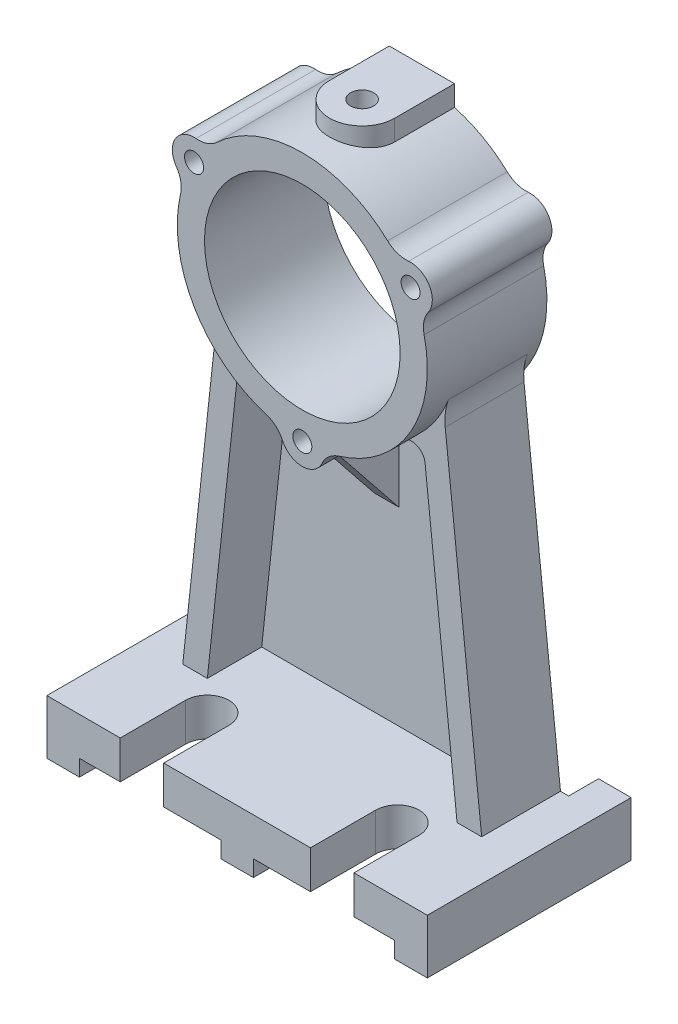
SolidWorks part; units mm, degrees
ref_plane "前视基准面" through (0, 0, 0) normal (0, 0, 1) x (1, 0, 0)
ref_plane "上视基准面" through (0, 0, 0) normal (0, 1, 0) x (1, 0, 0)
ref_plane "右视基准面" through (0, 0, 0) normal (1, 0, 0) x (0, 0, -1)
other "Configuration Table"
sketch "草图1" plane through (0, 0, 0) normal (0, 0, 1) x (1, 0, 0)
  circle A0 centre (0, 0) radius 46
extrude "凸台-拉伸1" add sketch "草图1" along normal blind 40 and the other way blind 4
sketch "草图2" plane through (0, 0, 0) normal (0, 0, 1) x (1, 0, 0)
  circle A0 centre (0, -46) radius 8
  circle A1 centre (0, 0) radius 46 construction
extrude "凸台-拉伸2" add sketch "草图2" along normal blind 40 and the other way blind 4
fillet "圆角1" radius 10 2 edges at (7.9697, -45.3043, 18) (-7.9697, -45.3043, 18)
pattern_circular "阵列(圆周)1" count 3 over 360 about axis through (0, 0, 0) along (0, 0, 1) of "圆角1", "凸台-拉伸2"
sketch "草图3" plane through (0, 0, 0) normal (0, 1, 0) x (1, 0, 0)
  line L0 (-12, 4) -> (12, 4)
  line L1 (12, 4) -> (12, -18)
  line L2 (31.3969, 4) -> (-31.3969, 4) construction
  line L3 (-12, 4) -> (-12, -18)
  arc A0 (-12, -18) -> (12, -18) centre (0, -18) ccw
  point P11 (0, -30)
  dimension "D2" = 12
  dimension "D1" = 34
  dimension "D3" = 12
extrude "凸台-拉伸3" add sketch "草图3" along normal blind 52
sketch "草图4" plane through (0, 0, 0) normal (0, 0, 1) x (1, 0, 0)
  line L0 (-55, -150) -> (55, -150)
  line L1 (41, -20.8567) -> (-41, -20.8567)
  line L2 (-55, -150) -> (-41, -20.8567)
  line L3 (41, -20.8567) -> (55, -150)
  arc A2 (-44.8133, 10.381) -> (-13.4164, -44) centre (0, 0) ccw construction
  point P3 (0, -150)
  point P7 (0, -20.8567)
  dimension "D1" = 150
  dimension "D2" = 82
extrude "凸台-拉伸4" add sketch "草图4" along normal blind 9
sketch "草图5" plane through (0, 0, 9) normal (0, 0, 1) x (1, 0, 0)
  line L0 (-41, -20.8567) -> (-55, -150) construction
  line L1 (-41, -20.8567) -> (-55, -150)
  line L2 (-32.0524, -21.8266) -> (-45.9473, -150)
  line L3 (-32.0524, -21.8266) -> (-41, -20.8567)
  line L4 (-55, -150) -> (-45.9473, -150)
  line L5 (-55, -150) -> (55, -150) construction
  line L6 (-32.0524, -21.8266) -> (-46.0524, -150.97) construction
  point P4 (-45.9473, -149.5346)
  dimension "D1" = 9
extrude "凸台-拉伸5" add sketch "草图5" along normal blind 20
mirror "镜向1" about plane through (0, 0, 0) normal (1, 0, 0) of "凸台-拉伸5"
fillet "圆角2" radius 20 2 edges at (-41, -20.8567, 14.5) (41, -20.8567, 14.5)
fillet "圆角3" radius 5 2 edges at (33.1442, -31.8977, 19) (-33.1442, -31.8977, 19)
sketch "草图6" plane through (0, 0, 0) normal (1, 0, 0) x (0, 0, -1)
  line L0 (-30, -54) -> (-7.5545, -82)
  line L1 (-40, -54) -> (-9, -54) construction
  line L2 (-40, -49.3623) -> (-40, -54) construction
  dimension "D1" = 10
  dimension "D2" = 82
rib "筋1" sketch "草图6" sketch "草图6" thickness 9 extrusion direction parallel to sketch draft on no parameters "D1"=9
sketch "草图7" plane through (0, 0, 0) normal (0, 0, 1) x (1, 0, 0)
  line L0 (-70, -150) -> (70, -150)
  line L1 (70, -150) -> (70, -170)
  line L2 (70, -170) -> (58, -170)
  line L3 (58, -170) -> (58, -164)
  line L4 (58, -164) -> (6, -164)
  line L5 (6, -164) -> (6, -170)
  line L6 (6, -170) -> (-6, -170)
  line L7 (-6, -170) -> (-6, -164)
  line L8 (-6, -164) -> (-58, -164)
  line L9 (-58, -164) -> (-58, -170)
  line L11 (-58, -170) -> (-70, -170)
  line L12 (-70, -170) -> (-70, -150)
  point P10 (0, -150)
  point P14 (0, 0)
  dimension "D1" = 20
  dimension "D2" = 140
  dimension "D3" = 116
  dimension "D4" = 12
  dimension "D5" = 12
  dimension "D6" = 12
  dimension "D7" = 6
  dimension "D8" = 52
extrude "凸台-拉伸6" add sketch "草图7" along normal blind 64 and the other way blind 11
sketch "草图8" plane through (0, -150, 0) normal (0, 1, 0) x (1, 0, 0)
  line L0 (58, 11) -> (58, -64) construction
  line L1 (-58, 11) -> (58, 11)
  line L2 (-58, 11) -> (-58, 0)
  line L3 (-58, 0) -> (58, 0)
  line L4 (58, 11) -> (58, 0)
  line L5 (-39.1195, -40) -> (-31.3969, -40) construction
  line L6 (-47.8372, -40) -> (-39.1195, -40) construction
  line L7 (-31.3969, -40) -> (31.3969, -40) construction
  line L8 (-43, -40) -> (-43, -64)
  line L9 (70, -64) -> (-70, -64) construction
  line L10 (-27, -40) -> (-27, -64)
  line L11 (-43, -64) -> (-27, -64)
  line L12 (43, -40) -> (43, -64)
  line L13 (27, -40) -> (27, -64)
  line L14 (27, -64) -> (43, -64)
  arc A0 (-43, -40) -> (-27, -40) centre (-35, -40) cw
  arc A1 (43, -40) -> (27, -40) centre (35, -40) ccw
  point P16 (0, 0)
  dimension "D1" = 35
  dimension "D2" = 70
extrude "切除-拉伸1" cut sketch "草图8" against normal blind 64 contours L10 L11 L8 A0 | L12 L14 L13 A1 | L3 L4 L1 L2
sketch "草图9" plane through (0, 0, 40) normal (0, 0, 1) x (1, 0, 0)
  circle A0 centre (0, 0) radius 36
  circle A1 centre (-39.8372, 23) radius 3.5
  circle A2 centre (39.8372, 23) radius 3.5
  circle A3 centre (0, -46) radius 3.5
  point P13 (0, 0)
  dimension "D1" = 3
extrude "切除-拉伸2" cut sketch "草图9" against normal blind 64
hole_wizard "M10 螺纹孔1" positions "3D草图1" profile "草图10" tap size "M10" standard "GB"
sketch3d "3D草图1"
  line L0 (0, 57.6795, 18) -> (0, 40.6409, 18) construction
  point P0 (0, 52, 18)
sketch "草图10" plane through (0, 52, 18) normal (1, 0, 0) x (0, 0, 1)
  line L0 (0, 0) -> (0, 16)
  line L1 (0, 16) -> (4.25, 16)
  line L2 (4.25, 16) -> (4.25, 0)
  line L5 (4.25, 0) -> (0, 0)
  line L11 (0, -6.35) -> (0, 107.95) construction
  dimension "通孔螺纹孔钻头直径" = 8.5
  dimension "通孔螺纹孔钻头深度" = 16
cosmetic thread "孔螺纹线1" parameters "D2"=10
